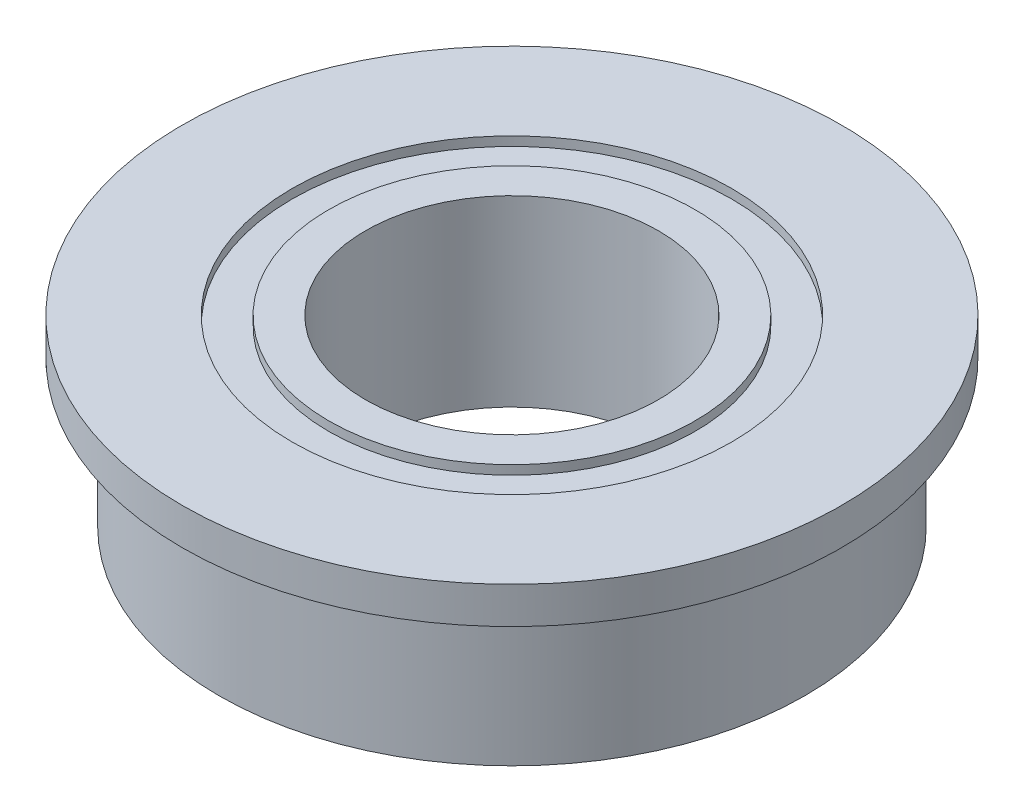
SolidWorks part; units mm, degrees
ref_plane "Front" through (0, 0, 0) normal (0, 0, 1) x (1, 0, 0)
ref_plane "Top" through (0, 0, 0) normal (0, 1, 0) x (1, 0, 0)
ref_plane "Right" through (0, 0, 0) normal (1, 0, 0) x (0, 0, -1)
sketch "Sketch1" plane through (0, 0, 0) normal (1, 0, 0) x (0, -1, 0)
  line L0 (-2.5, 9) -> (-1.5, 9)
  line L3 (-1.5, 9) -> (-1.5, 8)
  line L4 (-1.5, 8) -> (2.5, 8)
  line L5 (2.5, 8) -> (2.5, 6)
  line L6 (2.5, 6) -> (2.25, 6)
  line L8 (2.25, 6) -> (2.25, 5)
  line L9 (2.25, 5) -> (2.5, 5)
  line L10 (2.5, 5) -> (2.5, 4)
  line L11 (2.5, 4) -> (-2.5, 4)
  line L12 (-2.5, 4) -> (-2.5, 5)
  line L13 (-2.5, 5) -> (-2.25, 5)
  line L15 (-2.25, 5) -> (-2.25, 6)
  line L16 (-2.25, 6) -> (-2.5, 6)
  line L17 (-2.5, 6) -> (-2.5, 9)
  line L40 (0, 4) -> (0, 8) construction
  line L41 (0, 0) -> (4.007, 0) construction
  dimension "D1" = 8
  dimension "D2" = 16
  dimension "D3" = 18
  dimension "D4" = 1
  dimension "D5" = 5
  dimension "D6" = 1
  dimension "D7" = 0.25
  dimension "D8" = 1
revolve "Revolve1" add sketch "Sketch1" angle 360 about L41
